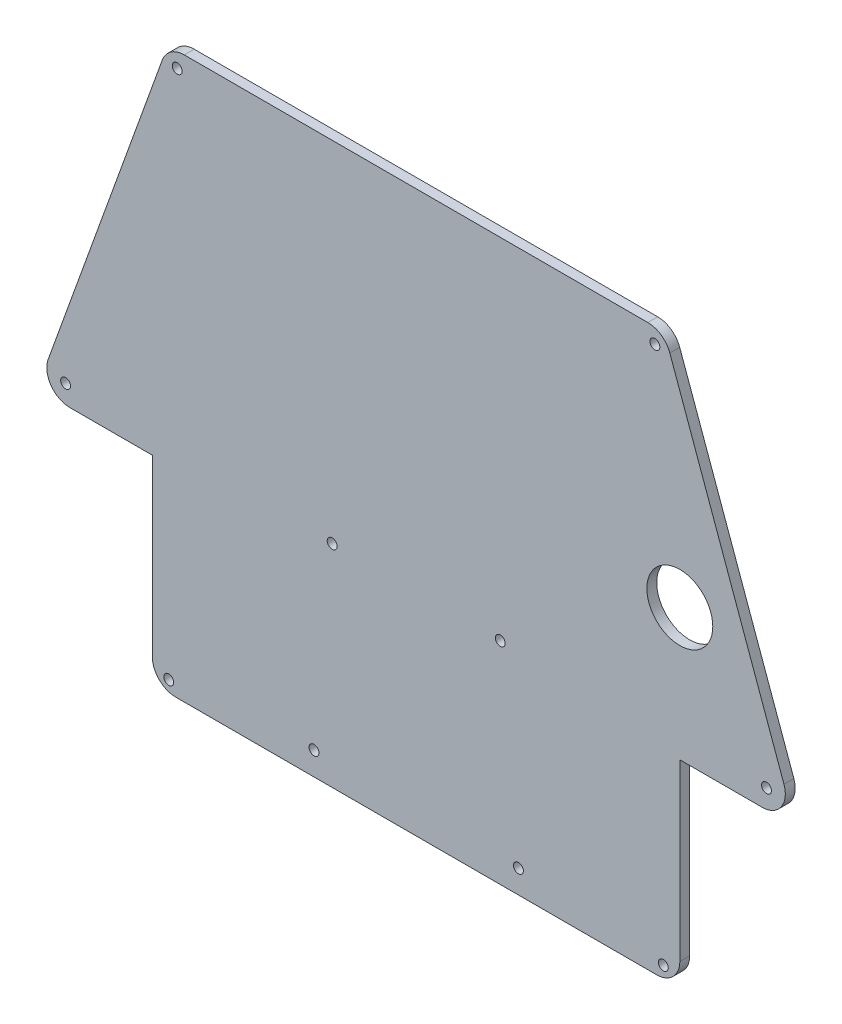
SolidWorks part; units mm, degrees
ref_plane "前视基准面" through (0, 0, 0) normal (0, 0, 1) x (1, 0, 0)
ref_plane "上视基准面" through (0, 0, 0) normal (0, 1, 0) x (1, 0, 0)
ref_plane "右视基准面" through (0, 0, 0) normal (1, 0, 0) x (0, 0, -1)
sketch "草图2" plane through (0, 0, 0) normal (0, 0, 1) x (1, 0, 0)
  line L0 (0.0477, 0) -> (0.0477, 60) construction
  line L1 (-72.9046, 0) -> (73, 0)
  line L3 (-70.2959, 170) -> (70.2959, 170)
  line L7 (-80, 7.0954) -> (-80, 60)
  line L8 (-80, 60) -> (-105, 60)
  line L9 (-111.5845, 69.3757) -> (-76.9701, 165.3127)
  line L10 (80, 7) -> (80, 60)
  line L11 (80, 60) -> (105, 60)
  line L12 (111.5845, 69.3757) -> (76.9701, 165.3127)
  arc A0 (105, 60) -> (111.5845, 69.3757) centre (105, 67) ccw
  arc A1 (73, 0) -> (80, 7) centre (73, 7) ccw
  arc A2 (-105, 60) -> (-111.5845, 69.3757) centre (-105, 67) cw
  arc A3 (-80, 7.0954) -> (-72.9046, 0) centre (-72.9046, 7.0954) ccw
  arc A4 (-76.9701, 165.3127) -> (-70.2959, 170) centre (-70.2959, 162.9046) cw
  arc A5 (76.9701, 165.3127) -> (70.2959, 170) centre (70.2959, 162.9046) ccw
  circle A6 centre (-30.9523, 7.0657) radius 1.5
  circle A7 centre (31.0477, 7.0657) radius 1.5
  circle A8 centre (-25.4523, 64.0657) radius 1.5
  circle A9 centre (25.5477, 64.0657) radius 1.5
  circle A14 centre (-72.4414, 165.3757) radius 1.5
  circle A15 centre (-106.2915, 65.7561) radius 1.5
  circle A16 centre (106.2915, 65.7561) radius 1.5
  circle A17 centre (72.4414, 165.3757) radius 1.5
  circle A24 centre (-75, 3.552) radius 1.5
  circle A25 centre (75, 3.552) radius 1.5
  circle A31 centre (80, 100) radius 10
  point P0 (0.0477, 0)
  point P31 (25.5477, 61.8665)
  point P32 (0, 0)
  point P33 (25.5477, 66.9844)
  point P34 (25.5477, 64.0657)
  dimension "D1" = 170
  dimension "D6" = 3
  dimension "D7" = 51
  dimension "D11" = 3
  dimension "D12" = 3
  dimension "D13" = 7
  dimension "D8" = 57
  dimension "D14" = 7
  dimension "D18" = 3
  dimension "D29" = 20
  dimension "D30" = 40
  dimension "D4" = 3
  dimension "D5" = 62
  dimension "D20" = 160
  dimension "D21" = 150
  dimension "D22" = 25
  dimension "D23" = 25
extrude "凸台-拉伸2" add sketch "草图2" along normal blind 3
